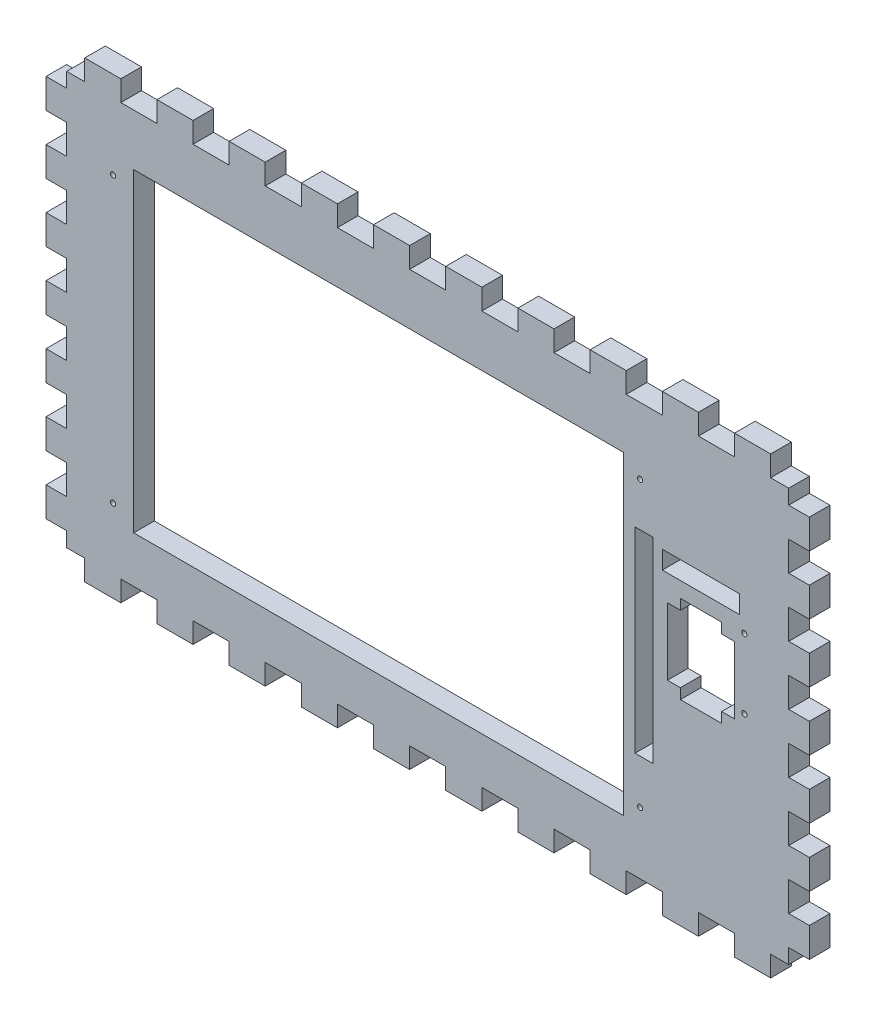
SolidWorks part; units mm, degrees
ref_plane "Piano frontale" through (0, 0, 0) normal (0, 0, 1) x (1, 0, 0)
ref_plane "Piano superiore" through (0, 0, 0) normal (0, 1, 0) x (1, 0, 0)
ref_plane "Piano destro" through (0, 0, 0) normal (1, 0, 0) x (0, 0, -1)
sketch "Schizzo1" plane through (0, 0, 0) normal (0, 0, 1) x (1, 0, 0)
  line L1 (0, 0) -> (140, 0)
  line L2 (0, 0) -> (0, 80)
  line L3 (0, 80) -> (140, 80)
  line L4 (140, 0) -> (140, 80)
  line L5 (13, 9) -> (108, 9)
  line L6 (13, 9) -> (13, 70)
  line L7 (13, 70) -> (108, 70)
  line L8 (108, 9) -> (108, 70)
  line L9 (116.5, 36) -> (129.5, 36)
  line L10 (116.5, 36) -> (116.5, 49)
  line L11 (116.5, 49) -> (129.5, 49)
  line L12 (129.5, 36) -> (129.5, 49)
  line L13 (116.5, 36) -> (129.5, 49) construction
  line L14 (116.5, 49) -> (129.5, 36) construction
  line L15 (119, 49) -> (127, 49)
  line L16 (119, 49) -> (119, 51)
  line L17 (119, 51) -> (127, 51)
  line L18 (127, 49) -> (127, 51)
  line L19 (119, 36) -> (127, 36)
  line L20 (119, 36) -> (119, 34)
  line L21 (119, 34) -> (127, 34)
  line L22 (127, 36) -> (127, 34)
  line L27 (115.5, 57.5) -> (130.5, 57.5)
  line L28 (115.5, 57.5) -> (115.5, 54)
  line L29 (115.5, 54) -> (130.5, 54)
  line L30 (130.5, 57.5) -> (130.5, 54)
  line L32 (110.2, 58.6) -> (113.7, 58.6)
  line L33 (110.2, 58.6) -> (110.2, 20.6)
  line L34 (110.2, 20.6) -> (113.7, 20.6)
  line L35 (113.7, 58.6) -> (113.7, 20.6)
  circle A0 centre (123, 42.5) radius 3.5
  circle A1 centre (131.4, 51.3) radius 0.5
  circle A2 centre (131.4, 37.8) radius 0.5
  circle A3 centre (111.2, 12) radius 0.5
  circle A4 centre (111.2, 67.1) radius 0.5
  circle A5 centre (9, 67.1) radius 0.5
  circle A6 centre (9, 12) radius 0.5
  point P23 (123, 49)
  point P24 (123, 51)
  point P29 (123, 57.5)
  point P34 (111.95, 58.6)
  dimension "D21" = 1
  dimension "D22" = 1
  dimension "D23" = 1
  dimension "D24" = 1
  dimension "D25" = 1
  dimension "D26" = 1
  dimension "D1" = 140
  dimension "D2" = 80
  dimension "D3" = 10
  dimension "D4" = 95
  dimension "D5" = 61
  dimension "D6" = 32
  dimension "D8" = 15
  dimension "D9" = 27.5
  dimension "D10" = 13
  dimension "D11" = 13
  dimension "D7" = 8
  dimension "D12" = 2
  dimension "D13" = 2
  dimension "D14" = 15
  dimension "D15" = 3.5
  dimension "D16" = 11.5
  dimension "D17" = 38
  dimension "D18" = 3.5
  dimension "D19" = 2.2
  dimension "D20" = 11.4
  dimension "D27" = 1.9
  dimension "D28" = 1.9
  dimension "D29" = 13.5
  dimension "D30" = 1.8
  dimension "D31" = 3.2
  dimension "D32" = 3.2
  dimension "D33" = 3
  dimension "D34" = 2.9
  dimension "D35" = 2.9
  dimension "D36" = 3
  dimension "D37" = 4
  dimension "D38" = 4
extrude "Estrusione-Estrusione1" add sketch "Schizzo1" along normal blind 4 contours L1 L4 L3 L2 L12 L9 L10 L11 L8 L5 L6 L7 | A0
sketch "Schizzo2" plane through (0, 0, 4) normal (0, 0, 1) x (1, 0, 0)
  line L1 (3.5, 80) -> (10.5, 80)
  line L2 (3.5, 80) -> (3.5, 84)
  line L3 (3.5, 84) -> (10.5, 84)
  line L4 (10.5, 80) -> (10.5, 84)
  line L5 (3.5, 0) -> (10.5, 0)
  line L6 (3.5, 0) -> (3.5, -4)
  line L7 (3.5, -4) -> (10.5, -4)
  line L8 (10.5, 0) -> (10.5, -4)
  line L11 (0, 0) -> (0, 80) construction
  line L12 (0, 80) -> (140, 80) construction
  line L13 (0, 0) -> (140, 0) construction
  dimension "D1" = 7
  dimension "D2" = 4
  dimension "D4" = 4
  dimension "D3" = 3.5
extrude "Estrusione-Estrusione2" add sketch "Schizzo2" against normal blind 4
pattern_linear "Ripetizione a L1" count 10 spacing 14 along (1, 0, 0) of "Estrusione-Estrusione2"
sketch "Schizzo3" plane through (0, 0, 4) normal (0, 0, 1) x (1, 0, 0)
  line L0 (140, 0) -> (140, 80) construction
  line L1 (0, 77.1429) -> (-4, 77.1429)
  line L2 (0, 77.1429) -> (0, 71.4286)
  line L3 (0, 71.4286) -> (-4, 71.4286)
  line L4 (-4, 77.1429) -> (-4, 71.4286)
  line L6 (140, 77.1429) -> (144, 77.1429)
  line L7 (140, 77.1429) -> (140, 71.4286)
  line L8 (140, 71.4286) -> (144, 71.4286)
  line L9 (144, 77.1429) -> (144, 71.4286)
  line L11 (0, 0) -> (0, 80) construction
  line L12 (0, 80) -> (3.5, 80) construction
  dimension "D4" = 4
  dimension "D1" = 5.7143
  dimension "D3" = 4
  dimension "D2" = 2.8571
extrude "Estrusione-Estrusione3" add sketch "Schizzo3" against normal blind 4
pattern_linear "Ripetizione a L2" count 7 spacing 11.4286 along (0, -1, 0) of "Estrusione-Estrusione3"
equation "\"WFront\"= 140mm"
equation "\"HFront\"= 80mm"
equation "\"DFront\"= 4mm"
equation "\"WLeft\"= 50mm"
equation "\"HLeft\"= 80mm"
equation "\"DLeft\"= 4mm"
equation "\"WTop\"= 140mm"
equation "\"HTop\"= 50mm"
equation "\"DTop\"= 4mm"
equation "\"N_Denti_W\"= 10"
equation "\"N_Denti_H\"= 7"
equation "\"N_Denti_D\"= 4"
equation "\"HDistDenti\"= \"HFront\" / \"N_Denti_H\""
equation "\"WDistDenti\"= \"WFront\" / \"N_Denti_W\""
equation "\"DDistDenti\"= \"WLeft\" / \"N_Denti_D\""
equation "\"HDenti\"= \"HDistDenti\" / 2"
equation "\"WDenti\"= \"WDistDenti\" / 2"
equation "\"DDenti\"= \"DDistDenti\" / 2"
equation "\"WDisplay\"= 95mm"
equation "\"HDisplay\"= 61mm"
equation "\"CEnc\"= 7mm"
equation "\"Display_to_Enc_W\"= 11.5 + \"CEnc\" / 2"
equation "\"Display_to_Dx\"= 32mm"
equation "\"Display_to_Top\"= 10mm"
equation "\"Display_to_Enc_H\"= 24 + \"CEnc\" / 2"
equation "\"D1@Schizzo1\"=\"WFront\""
equation "\"D2@Schizzo1\"=\"HFront\""
equation "\"D3@Schizzo1\"=\"Display_to_Top\""
equation "\"D4@Schizzo1\"=\"WDisplay\""
equation "\"D5@Schizzo1\"=\"HDisplay\""
equation "\"D1@Estrusione-Estrusione1\"=\"DFront\""
equation "\"D1@Schizzo2\"=\"WDenti\""
equation "\"D2@Schizzo2\"=\"DTop\""
equation "\"D4@Schizzo2\"=\"DTop\""
equation "\"D1@Estrusione-Estrusione2\"=\"DFront\""
equation "\"D3@Ripetizione a L1\"=\"WDistDenti\""
equation "\"D1@Ripetizione a L1\"=\"N_Denti_W\""
equation "\"D1@Schizzo3\"=\"HDenti\""
equation "\"D4@Schizzo3\"=\"DLeft\""
equation "\"D1@Estrusione-Estrusione3\"=\"DFront\""
equation "\"D3@Ripetizione a L2\"=\"HDistDenti\""
equation "\"D1@Ripetizione a L2\"=\"N_Denti_H\""
equation "\"D3@Schizzo2\"=\"WDenti\"/2"
equation "\"D3@Schizzo3\"=\"DLeft\""
equation "\"D2@Schizzo3\"=\"HDenti\"/2"
